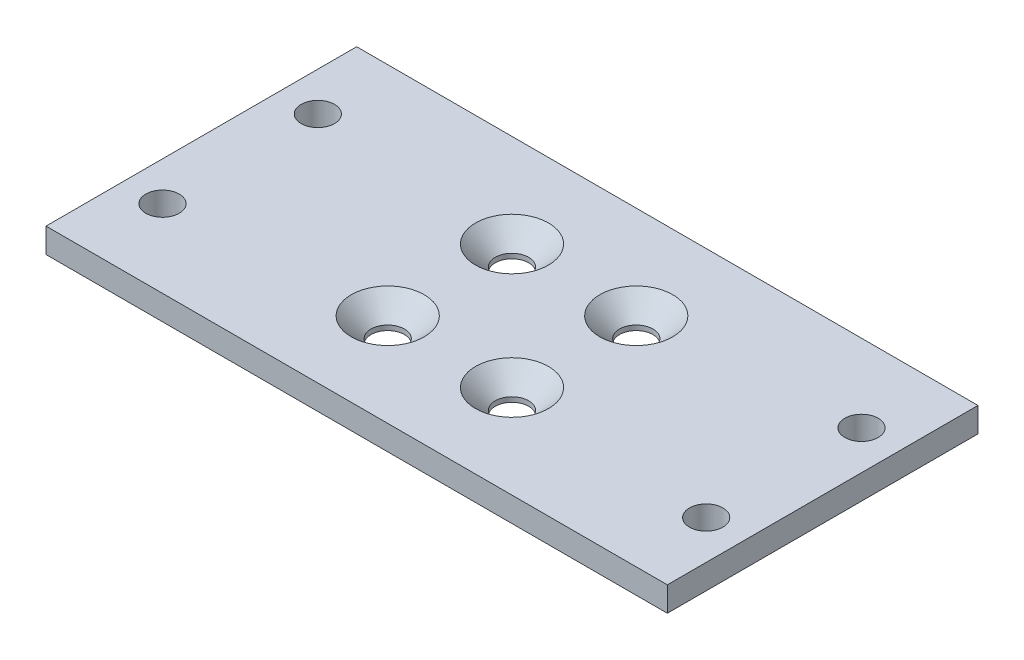
SolidWorks part; units mm, degrees
material "6061 Alloy"
ref_plane "Front Plane" through (0, 0, 0) normal (0, 0, 1) x (1, 0, 0)
ref_plane "Top Plane" through (0, 0, 0) normal (0, 1, 0) x (1, 0, 0)
ref_plane "Right Plane" through (0, 0, 0) normal (1, 0, 0) x (0, 0, -1)
sketch "Sketch2" plane through (0, 0, 0) normal (0, 1, 0) x (1, 0, 0)
  line L1 (-40, -20) -> (40, -20)
  line L2 (-40, -20) -> (-40, 20)
  line L3 (-40, 20) -> (40, 20)
  line L4 (40, -20) -> (40, 20)
  line L5 (-40, -20) -> (40, 20) construction
  line L6 (-40, 20) -> (40, -20) construction
  point P0 (0, 0)
  dimension "D1" = 40
  dimension "D2" = 80
extrude "Boss-Extrude1" add sketch "Sketch2" along normal blind 3.175
sketch "Sketch3" plane through (0, 3.175, 0) normal (0, 1, 0) x (1, 0, 0)
  line L0 (-40, 20) -> (-40, -20) construction
  line L1 (40, 20) -> (-40, 20) construction
  line L2 (0, 20) -> (0, 0) construction
  line L3 (0, 0) -> (-40, 0) construction
  point P0 (-35, 10)
  point P8 (35, 10)
  point P10 (35, -10)
  point P11 (-35, -10)
  dimension "D1" = 5
  dimension "D2" = 10
hole_wizard "M4 Clearance Hole1" positions "Sketch3" profile "Sketch4" hole size "M4" standard "ANSI Metric" end condition through all
sketch "Sketch4" plane through (-35, 3.175, -10) normal (1, 0, 0) x (0, 0, 1)
  line L0 (0, 0) -> (0, 3.175)
  line L1 (0, 3.175) -> (2.15, 3.175)
  line L2 (2.15, 3.175) -> (2.15, 0)
  line L5 (2.15, 0) -> (0, 0)
  line L11 (0, -6.35) -> (0, 107.95) construction
  dimension "Thru Hole Dia." = 4.3
  dimension "Thru Hole Depth" = 3.175
sketch "Sketch5" plane through (0, 3.175, 0) normal (0, 1, 0) x (1, 0, 0)
  point P0 (-8, 8)
  point P1 (0, 0)
  point P6 (8, 8)
  point P7 (8, -8)
  point P8 (-8, -8)
  dimension "D1" = 8
  dimension "D2" = 8
  dimension "D3" = 4
hole_wizard "CSK for M4 Flat Head Machine Screw2" positions "Sketch5" profile "Sketch6" countersink size "M4" standard "ANSI Metric"
sketch "Sketch6" plane through (-8, 3.175, -8) normal (1, 0, 0) x (0, 0, 1)
  line L0 (0, 0) -> (0, 3.175)
  line L1 (0, 3.175) -> (2.15, 3.175)
  line L2 (2.15, 3.175) -> (2.15, 2.55)
  line L3 (2.15, 2.55) -> (4.7, 0)
  line L5 (4.7, 0) -> (0, 0)
  line L6 (-2.15, 2.55) -> (-4.7, 0) construction
  line L11 (0, -6.35) -> (0, 107.95) construction
  dimension "Thru Hole Dia." = 4.3
  dimension "Thru Hole Depth" = 3.175
  dimension "Near C'Sink Dia." = 9.4
  dimension "Near C'Sink Angle" = 90
